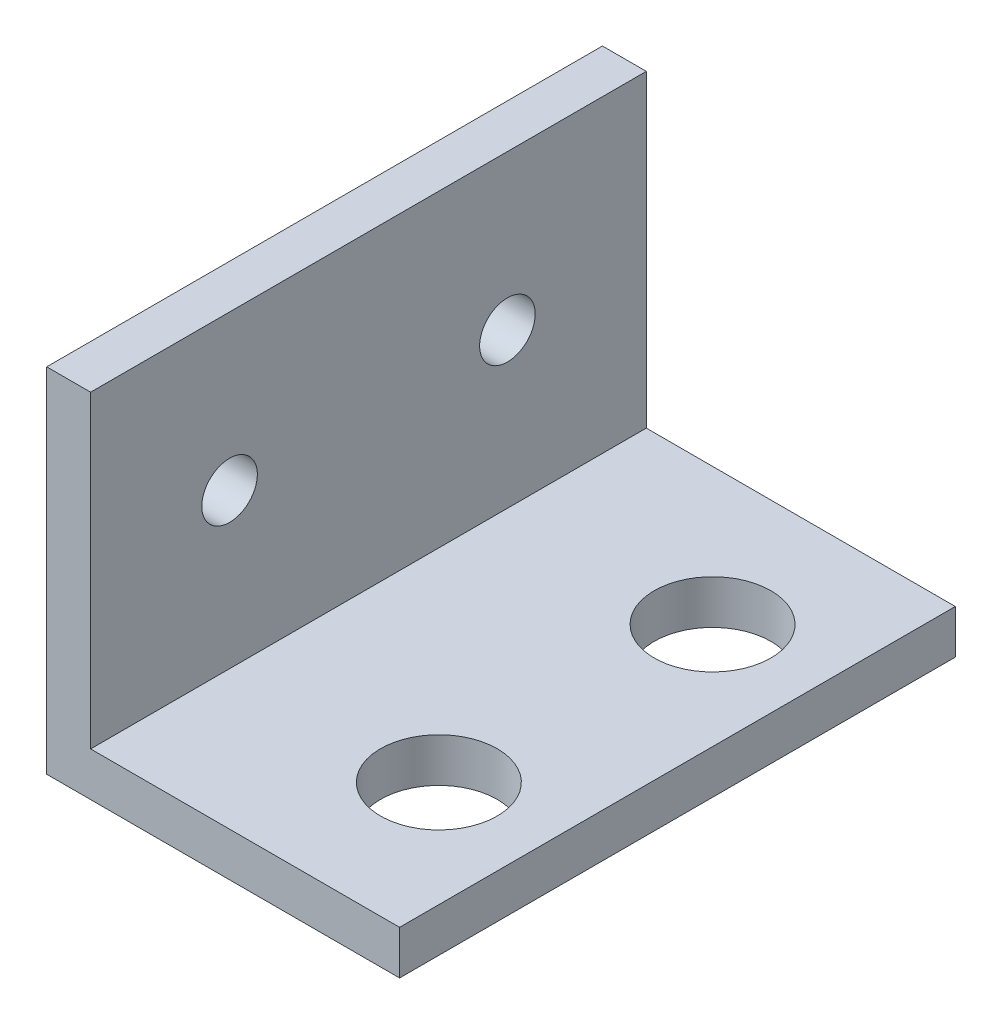
SolidWorks part; units mm, degrees
ref_plane "Front Plane" through (0, 0, 0) normal (0, 0, 1) x (1, 0, 0)
ref_plane "Top Plane" through (0, 0, 0) normal (0, 1, 0) x (1, 0, 0)
ref_plane "Right Plane" through (0, 0, 0) normal (1, 0, 0) x (0, 0, -1)
sketch "Sketch1" plane through (0, 0, 0) normal (0, 0, 1) x (1, 0, 0)
  line L0 (0, 0) -> (0, 12.7)
  line L1 (0, 0) -> (12.7, 0)
  line L2 (1.58, 1.58) -> (12.7, 1.58)
  line L3 (1.58, 1.58) -> (1.58, 12.7)
  line L4 (0, 12.7) -> (1.58, 12.7)
  line L5 (12.7, 1.58) -> (12.7, 0)
  dimension "D1" = 12.7
  dimension "D2" = 12.7
  dimension "D3" = 1.58
extrude "Boss-Extrude1" add sketch "Sketch1" along normal blind 20
sketch "Sketch2" plane through (0, 0, 0) normal (-1, 0, 0) x (0, 0, 1)
  line L0 (0, 1.58) -> (20, 1.58)
  line L1 (0, 12.7) -> (0, 0) construction
  line L2 (20, 12.7) -> (20, 0) construction
  line L3 (10, 1.58) -> (10, 12.7)
  line L4 (20, 12.7) -> (0, 12.7) construction
  line L5 (10, 7.14) -> (0, 7.14)
  line L6 (10, 7.14) -> (20, 7.14)
  circle A0 centre (5, 7.14) radius 1
  circle A1 centre (15, 7.14) radius 1
  dimension "D1" = 2
  dimension "D2" = 2
extrude "Cut-Extrude1" cut sketch "Sketch2" against normal up to next contours L5 A0 | L5 A0 | L6 A1 | L6 A1
sketch "Sketch3" plane through (0, 0, 0) normal (0, -1, 0) x (1, 0, 0)
  line L0 (6.6, 18.7) -> (6.6, 15.875)
  line L1 (6.6, 13.675) -> (6.6, 6.025)
  line L2 (6.6, 3.825) -> (6.6, 1)
  line L3 (0, 20) -> (0, 0)
  line L4 (0, 20) -> (12.7, 20)
  line L5 (0, 0) -> (12.7, 0)
  line L6 (12.7, 20) -> (12.7, 0) construction
  arc A0 (6.6, 1) -> (7.6, 0) centre (7.6, 1) ccw
  arc A1 (7.6, 19.7) -> (6.6, 18.7) centre (7.6, 18.7) ccw
  arc A2 (7.2336, 13.4827) -> (7.2336, 16.0673) centre (8.8889, 14.775) ccw
  arc A3 (7.2336, 3.6327) -> (7.2336, 6.2173) centre (8.8889, 4.925) ccw
  circle A4 centre (8.8889, 14.775) radius 2.1
  circle A5 centre (8.8889, 4.925) radius 2.1
  dimension "D1" = 1
  dimension "D2" = 2.1
  dimension "D3" = 3.8111
  dimension "D4" = 5.4664
  dimension "D5" = 6.1
  dimension "D6" = 12.7
  dimension "D7" = 3.6327
  dimension "D8" = 3.825
  dimension "D9" = 13.4827
  dimension "D10" = 6.025
  dimension "D11" = 15.875
  dimension "D13" = 13.675
  dimension "D18" = 20
extrude "Cut-Extrude2" cut sketch "Sketch3" against normal up to next contours A3 A5 | A2 A4
